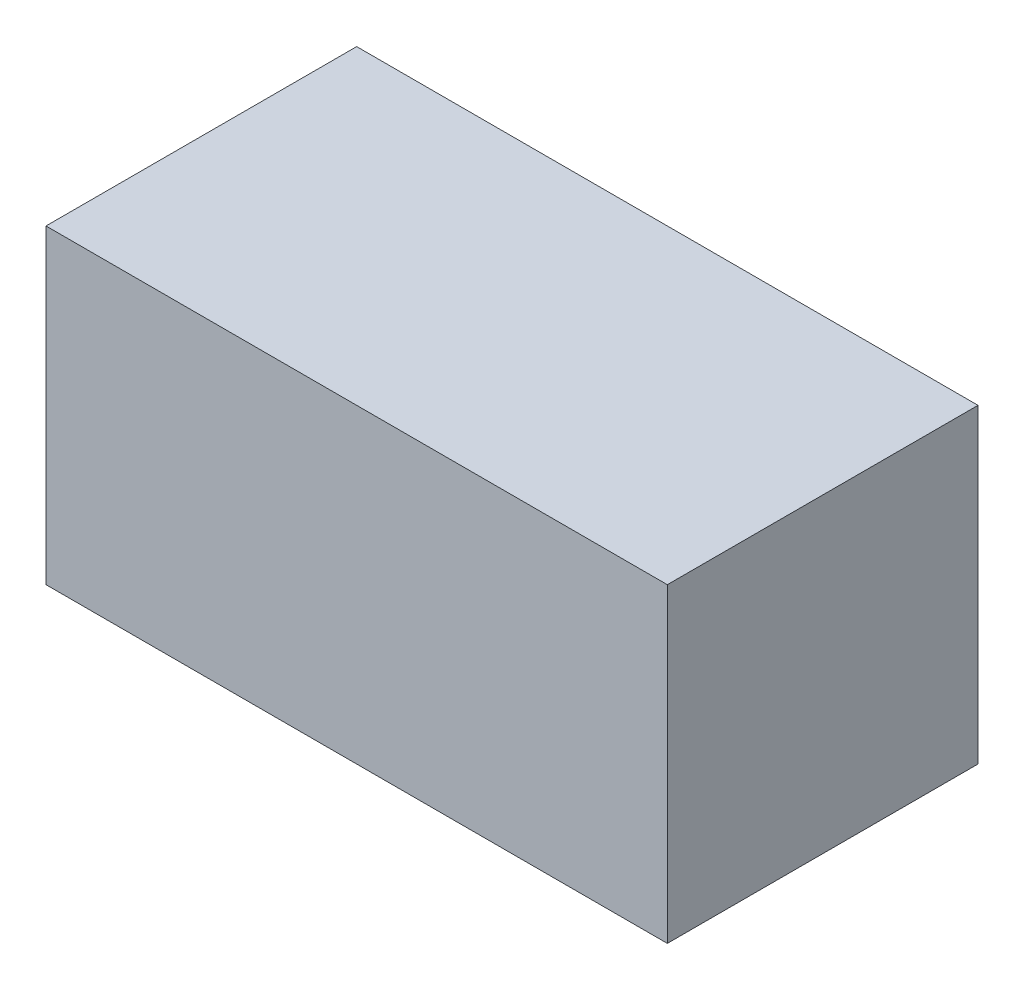
SolidWorks part; units mm, degrees
ref_plane "Plan de face" through (0, 0, 0) normal (0, 0, 1) x (1, 0, 0)
ref_plane "Plan de dessus" through (0, 0, 0) normal (0, 1, 0) x (1, 0, 0)
ref_plane "Plan de droite" through (0, 0, 0) normal (1, 0, 0) x (0, 0, -1)
sketch "Esquisse1" plane through (0, 0, 0) normal (0, 0, 1) x (1, 0, 0)
  line L1 (0, 0) -> (8, 0)
  line L2 (0, 0) -> (0, 4)
  line L3 (0, 4) -> (8, 4)
  line L4 (8, 0) -> (8, 4)
  dimension "D1" = 4
  dimension "D2" = 8
extrude "Extrusion1" add sketch "Esquisse1" along normal blind 4
